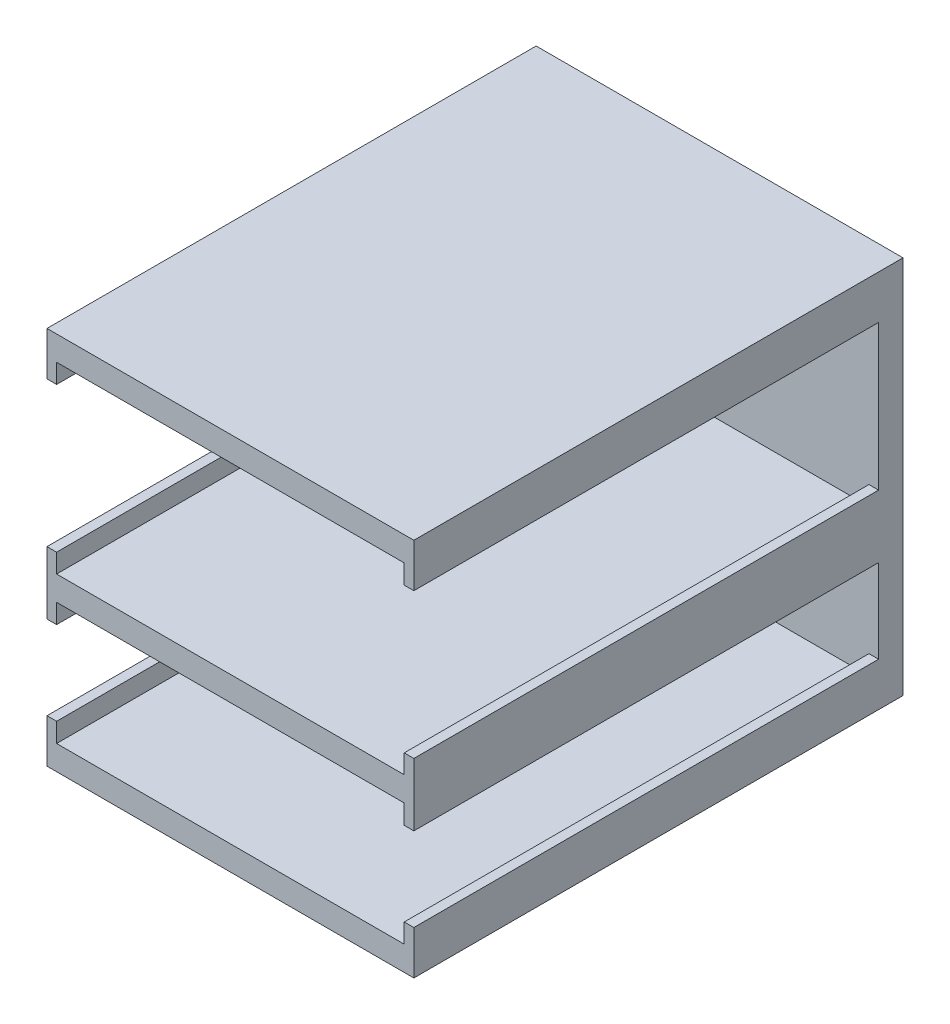
SolidWorks part; units mm, degrees
ref_plane "Alzado" through (0, 0, 0) normal (0, 0, 1) x (1, 0, 0)
ref_plane "Planta" through (0, 0, 0) normal (0, 1, 0) x (1, 0, 0)
ref_plane "Vista lateral" through (0, 0, 0) normal (1, 0, 0) x (0, 0, -1)
sketch "Croquis1" plane through (0, 0, 0) normal (0, 1, 0) x (1, 0, 0)
  line L1 (38.1, -50.8) -> (-38.1, -50.8)
  line L2 (38.1, -50.8) -> (38.1, 50.8)
  line L3 (38.1, 50.8) -> (-38.1, 50.8)
  line L4 (-38.1, -50.8) -> (-38.1, 50.8)
  line L5 (38.1, -50.8) -> (-38.1, 50.8) construction
  line L6 (38.1, 50.8) -> (-38.1, -50.8) construction
  point P0 (0, 0)
  dimension "D1" = 101.6
  dimension "D2" = 76.2
extrude "Saliente-Extruir1" add sketch "Croquis1" along normal blind 78.74
sketch "Croquis2" plane through (0, 0, 50.8) normal (0, 0, 1) x (1, 0, 0)
  line L0 (0, 0) -> (0, 78.74) construction
  line L1 (-38.1, 0) -> (38.1, 0) construction
  line L2 (-38.1, 78.74) -> (38.1, 78.74) construction
  line L4 (-38.1, 5.08) -> (38.1, 5.08)
  line L5 (-38.1, 5.08) -> (-38.1, 30.48)
  line L6 (-38.1, 30.48) -> (38.1, 30.48)
  line L7 (38.1, 5.08) -> (38.1, 30.48)
  point P10 (0, 30.48)
  dimension "D1" = 25.4
  dimension "D2" = 76.2
  dimension "D3" = 5.08
extrude "Cortar-Extruir1" cut sketch "Croquis2" against normal blind 96.52
sketch "Croquis3" plane through (0, 0, 50.8) normal (0, 0, 1) x (1, 0, 0)
  line L0 (0, 0) -> (0, 78.74) construction
  line L1 (-38.1, 0) -> (38.1, 0) construction
  line L2 (-38.1, 78.74) -> (38.1, 78.74) construction
  line L3 (38.1, 30.48) -> (-38.1, 30.48) construction
  line L4 (-38.1, 35.56) -> (38.1, 35.56)
  line L5 (-38.1, 35.56) -> (-38.1, 73.66)
  line L6 (-38.1, 73.66) -> (38.1, 73.66)
  line L7 (38.1, 35.56) -> (38.1, 73.66)
  point P10 (0, 73.66)
  dimension "D1" = 38.1
  dimension "D2" = 5.08
  dimension "D3" = 76.2
extrude "Cortar-Extruir2" cut sketch "Croquis3" against normal blind 96.52
sketch "Croquis4" plane through (0, 5.08, 0) normal (0, 1, 0) x (1, 0, 0)
  line L0 (-38.1, 45.72) -> (38.1, 45.72) construction
  line L1 (-38.1, -50.8) -> (-36.1, -50.8)
  line L2 (-38.1, -50.8) -> (-38.1, 45.72)
  line L3 (-38.1, 45.72) -> (-36.1, 45.72)
  line L4 (-36.1, -50.8) -> (-36.1, 45.72)
  dimension "D1" = 2
extrude "Saliente-Extruir3" add sketch "Croquis4" along normal through all
sketch "Croquis6" plane through (-38.1, 0, 0) normal (-1, 0, 0) x (0, 0, 1)
  line L0 (0, 0) -> (0, 5.08) construction
  line L1 (-50.8, 0) -> (50.8, 0) construction
  line L2 (0, 5.08) -> (0, 9.08) construction
  line L3 (50.8, 78.74) -> (50.8, 0) construction
  line L4 (50.8, 30.4594) -> (50.8, 26.4594) construction
  line L5 (50.8, 30.4594) -> (-50.8, 30.4594) construction
  line L6 (-50.8, 78.74) -> (-50.8, 0) construction
  line L7 (-50.8, 30.4594) -> (-50.8, 26.4594) construction
  line L8 (-50.8, 0) -> (50.8, 0) construction
  line L9 (50.8, 0) -> (50.8, 26.4594) construction
  line L10 (-45.72, 26.4594) -> (-45.72, 9.08)
  line L11 (50.8, 26.4594) -> (-45.72, 26.4594)
  line L12 (50.8, 26.4594) -> (50.8, 9.08)
  line L13 (50.8, 9.08) -> (-45.72, 9.08)
  line L15 (-50.8, 9.08) -> (-50.8, 0) construction
  dimension "D1" = 5.08
  dimension "D2" = 4
  dimension "D3" = 4
  dimension "D4" = 5.08
extrude "Cortar-Extruir4" cut sketch "Croquis6" against normal blind 4
sketch "Croquis7" plane through (-38.1, 0, 0) normal (-1, 0, 0) x (0, 0, 1)
  line L0 (50.8, 78.74) -> (50.8, 26.4594) construction
  line L1 (50.8, 39.4957) -> (-44.7634, 39.4957)
  line L2 (50.8, 39.4957) -> (50.8, 69.66)
  line L3 (50.8, 73.66) -> (-44.7634, 73.66) construction
  line L5 (-50.8, 78.74) -> (50.8, 78.74) construction
  line L6 (50.8, 35.4957) -> (-50.8, 35.4957) construction
  line L7 (-50.8, 78.74) -> (-50.8, 0) construction
  line L8 (-44.7634, 69.66) -> (50.8, 69.66)
  line L9 (-44.7634, 73.66) -> (-50.8, 73.66) construction
  line L10 (-45.72, 26.4594) -> (-45.72, 78.74) construction
  line L11 (-44.7634, 69.66) -> (-45.72, 69.66)
  line L12 (-45.72, 69.66) -> (-45.72, 39.4957)
  line L13 (-45.72, 39.4957) -> (-44.7634, 39.4957)
  dimension "D1" = 5.08
  dimension "D2" = 4
  dimension "D3" = 4
extrude "Cortar-Extruir5" cut sketch "Croquis7" against normal blind 4
mirror "Simetría1" about plane through (0, 0, 0) normal (1, 0, 0) of "Saliente-Extruir3", "Cortar-Extruir4", "Cortar-Extruir5"
sketch "Croquis8" plane through (0, 0, -45.72) normal (0, 0, 1) x (1, 0, 0)
  line L0 (-38.1, 26.4594) -> (-36.1, 26.4594)
  line L1 (-36.1, 26.4594) -> (-36.1, 30.48)
  line L2 (-36.1, 30.48) -> (36.1, 30.48)
  line L3 (36.1, 30.48) -> (36.1, 26.4594)
  line L4 (36.1, 26.4594) -> (38.1, 26.4594)
  line L5 (38.1, 26.4594) -> (38.1, 9.08)
  line L6 (38.1, 9.08) -> (36.1, 9.08)
  line L7 (36.1, 9.08) -> (36.1, 5.08)
  line L8 (36.1, 5.08) -> (-36.1, 5.08)
  line L9 (-36.1, 5.08) -> (-36.1, 9.08)
  line L10 (-36.1, 9.08) -> (-38.1, 9.08)
  line L11 (-38.1, 9.08) -> (-38.1, 26.4594)
  dimension "D1" = 17.3794
  dimension "D2" = 72.2
  dimension "D3" = 4
  dimension "D4" = 2
sketch "Croquis9" plane through (0, 5.08, 0) normal (0, 1, 0) x (1, 0, 0)
  line L0 (0, 45.72) -> (0, -50.8) construction
  line L1 (36.1, 45.72) -> (-36.1, 45.72) construction
  line L2 (-38.1, -50.8) -> (38.1, -50.8) construction
  dimension "D1" = 96.52
sketch "Croquis10" plane through (0, 0, -45.72) normal (0, 0, 1) x (1, 0, 0)
  line L0 (-36.1, 69.66) -> (-36.1, 73.66)
  line L1 (-36.1, 73.66) -> (36.1, 73.66)
  line L2 (36.1, 73.66) -> (36.1, 69.66)
  line L3 (36.1, 69.66) -> (38.1, 69.66)
  line L4 (38.1, 69.66) -> (38.1, 39.4957)
  line L5 (38.1, 39.4957) -> (36.1, 39.4957)
  line L6 (36.1, 39.4957) -> (36.1, 35.56)
  line L7 (36.1, 35.56) -> (-36.1, 35.56)
  line L8 (-36.1, 35.56) -> (-36.1, 39.4957)
  line L9 (-36.1, 39.4957) -> (-38.1, 39.4957)
  line L10 (-38.1, 39.4957) -> (-38.1, 69.66)
  dimension "D1" = 30.1643
  dimension "D2" = 2
  dimension "D3" = 3.9357
  dimension "D4" = 72.2
